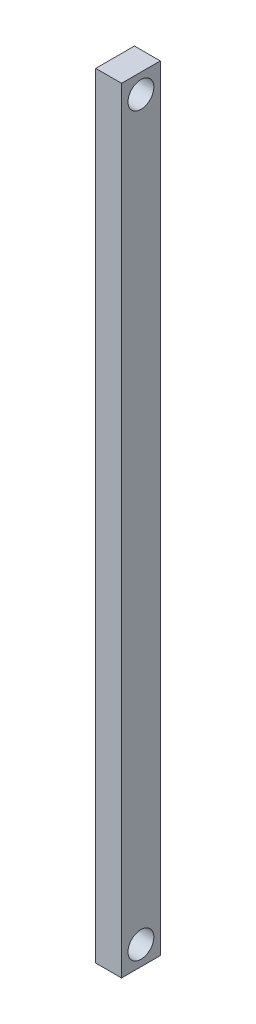
SolidWorks part; units mm, degrees
material "Plain Carbon Steel"
ref_plane "Front Plane" through (0, 0, 0) normal (1, 0, 0) x (0, 1, 0)
ref_plane "Top Plane" through (0, 0, 0) normal (0, 0, 1) x (0, 1, 0)
ref_plane "Right Plane" through (0, 0, 0) normal (0, 1, 0) x (-1, 0, 0)
sketch "Sketch1" plane through (0, 0, 0) normal (1, 0, 0) x (0, 1, 0)
  line L0 (0, 0) -> (300, 0)
  line L1 (300, 0) -> (300, 15)
  line L2 (300, 15) -> (0, 15)
  line L3 (0, 15) -> (0, 0)
  dimension "D1" = 15
  dimension "D2" = 300
extrude "Boss-Extrude1" add sketch "Sketch1" along normal blind 10
sketch "Sketch3" plane through (0, 0, 0) normal (1, 0, 0) x (0, 1, 0)
  line L0 (300, 15) -> (0, 15) construction
  line L1 (0, 15) -> (0, 0) construction
  circle A0 centre (7.5, 7.5) radius 5
  dimension "D1" = 10
  dimension "D2" = 7.5
  dimension "D3" = 7.5
extrude "Cut-Extrude1" cut sketch "Sketch3" along normal blind 10
sketch "Sketch4" plane through (10, 0, 0) normal (1, 0, 0) x (0, 1, 0)
  line L0 (300, 15) -> (0, 15) construction
  line L1 (300, 0) -> (300, 15) construction
  circle A0 centre (292.5, 7.5) radius 5
  dimension "D1" = 10
  dimension "D2" = 7.5
  dimension "D3" = 7.5
extrude "Cut-Extrude2" cut sketch "Sketch4" against normal blind 10
